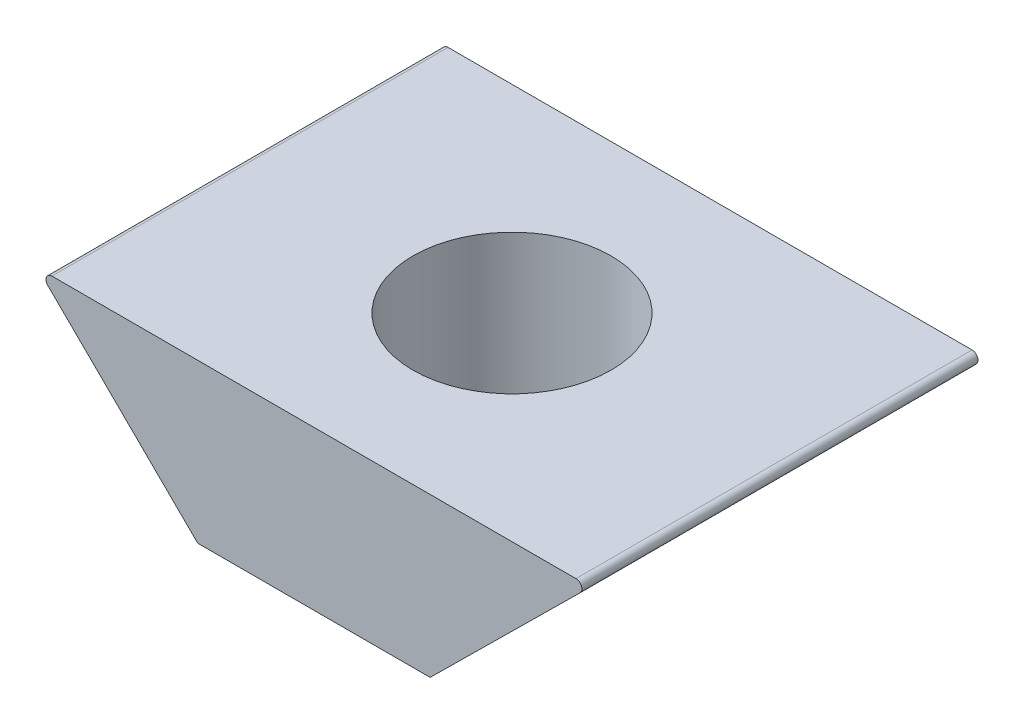
SolidWorks part; units mm, degrees
ref_plane "Front Plane" through (0, 0, 0) normal (0, 0, 1) x (1, 0, 0)
ref_plane "Top Plane" through (0, 0, 0) normal (0, 1, 0) x (1, 0, 0)
ref_plane "Right Plane" through (0, 0, 0) normal (1, 0, 0) x (0, 0, -1)
sketch "Sketch1" plane through (0, 0, 0) normal (0, 0, 1) x (1, 0, 0)
  line L0 (-18.2838, 4.9382) -> (-14.8657, 4.9382) construction
  line L1 (-14.7603, 4.6815) -> (-18.5469, 0.9382) construction
  line L2 (-18.5469, 0.9382) -> (-24.4133, 0.9382) construction
  line L3 (-28.0945, 4.9382) -> (-24.6764, 4.9382) construction
  line L4 (-24.4133, 0.9382) -> (-28.1999, 4.6815) construction
  line L5 (-18.2838, 4.9382) -> (-14.8657, 4.9382)
  line L6 (-14.7603, 4.6815) -> (-18.5469, 0.9382)
  line L7 (-18.5469, 0.9382) -> (-24.4133, 0.9382)
  line L8 (-28.0945, 4.9382) -> (-24.6764, 4.9382)
  line L9 (-24.4133, 0.9382) -> (-28.1999, 4.6815)
  line L10 (-24.6764, 4.9382) -> (-18.2838, 4.9382)
  arc A0 (-14.7603, 4.6815) -> (-14.8657, 4.9382) centre (-14.8657, 4.7882) ccw construction
  arc A1 (-28.0945, 4.9382) -> (-28.1999, 4.6815) centre (-28.0945, 4.7882) ccw construction
  arc A2 (-14.7603, 4.6815) -> (-14.8657, 4.9382) centre (-14.8657, 4.7882) ccw
  arc A3 (-28.0945, 4.9382) -> (-28.1999, 4.6815) centre (-28.0945, 4.7882) ccw
extrude "Boss-Extrude1" add sketch "Sketch1" along normal blind 10
sketch "Sketch2" plane through (0, 4.9382, 0) normal (0, 1, 0) x (1, 0, 0)
  line L0 (-28.0945, 0) -> (-14.8657, -10) construction
  line L1 (-14.8657, 0) -> (-28.0945, -10) construction
  circle A0 centre (-21.4801, -5) radius 2.5
  dimension "D1" = 5
extrude "Cut-Extrude1" cut sketch "Sketch2" against normal through all
